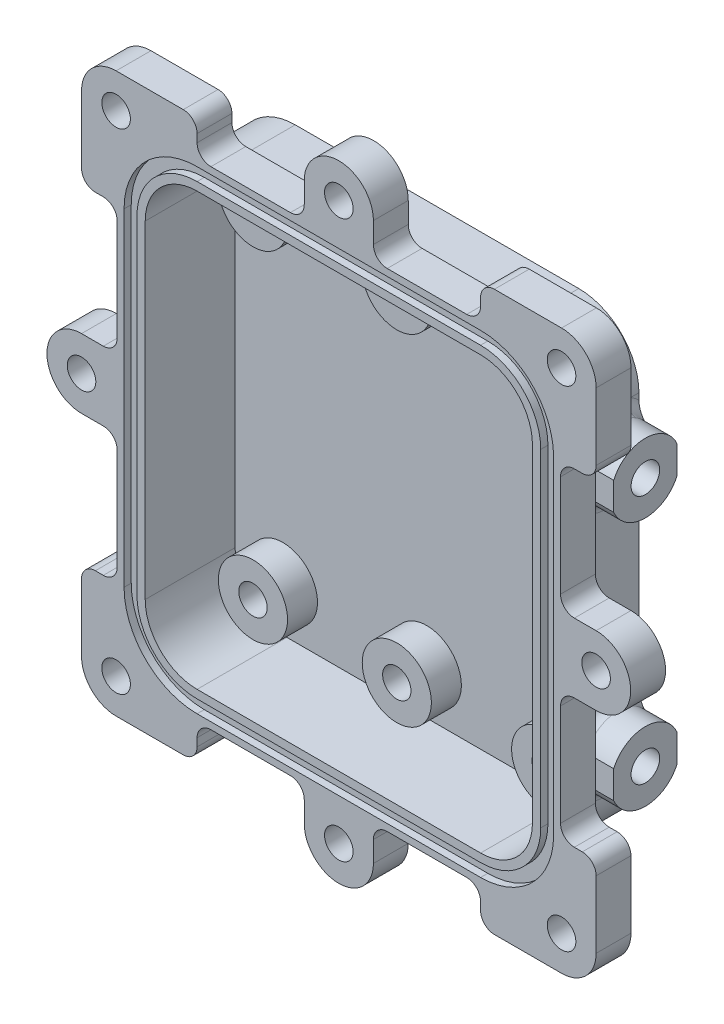
SolidWorks part; units mm, degrees
material "ABS"
ref_plane "X-Y Datum" through (0, 0, 0) normal (0, 0, 1) x (1, 0, 0)
ref_plane "X-Z Datum" through (0, 0, 0) normal (0, 1, 0) x (1, 0, 0)
ref_plane "Y-Z Datum" through (0, 0, 0) normal (1, 0, 0) x (0, 0, -1)
sketch "Sketch1" plane through (0, 0, 0) normal (0, 0, 1) x (1, 0, 0)
  line L0 (26.035, 143.51) -> (78.105, 143.51)
  line L5 (20.066, 67.818) -> (84.074, 67.818) construction
  line L6 (20.066, 67.818) -> (20.066, 139.954) construction
  line L7 (20.066, 139.954) -> (84.074, 139.954) construction
  line L8 (84.074, 67.818) -> (84.074, 139.954) construction
  line L9 (20.066, 67.818) -> (84.074, 139.954) construction
  line L10 (20.066, 139.954) -> (84.074, 67.818) construction
  line L11 (87.63, 73.787) -> (87.63, 133.985)
  line L12 (26.035, 64.262) -> (78.105, 64.262)
  line L13 (16.51, 73.787) -> (16.51, 133.985)
  line L14 (16.51, 143.51) -> (87.63, 143.51) construction
  line L15 (87.63, 64.262) -> (87.63, 143.51) construction
  line L16 (16.51, 64.262) -> (87.63, 64.262) construction
  line L17 (16.51, 64.262) -> (16.51, 143.51) construction
  circle A0 centre (25.292, 135.128) radius 2.1 construction
  circle A1 centre (51.708, 135.128) radius 2.1 construction
  circle A2 centre (79.14, 135.128) radius 2.1 construction
  circle A3 centre (51.708, 72.644) radius 2.1 construction
  circle A4 centre (79.14, 72.644) radius 2.1 construction
  circle A5 centre (25.292, 72.644) radius 2.1 construction
  arc A6 (78.105, 143.51) -> (87.63, 133.985) centre (78.105, 133.985) cw
  arc A7 (87.63, 73.787) -> (78.105, 64.262) centre (78.105, 73.787) cw
  arc A8 (26.035, 64.262) -> (16.51, 73.787) centre (26.035, 73.787) cw
  arc A9 (26.035, 143.51) -> (16.51, 133.985) centre (26.035, 133.985) ccw
  point P18 (52.07, 103.886)
  dimension "D2" = 9.525
  dimension "D1" = 3.556
extrude "Boss-Extrude1" add sketch "Sketch1" along normal blind 16.51 contours L13 A9 L0 A6 L11 A7 L12 A8
shell "Shell1" thickness 1.524
sketch "Sketch2" plane through (0, 0, 0) normal (0, 0, 1) x (1, 0, 0)
  circle A0 centre (25.292, 135.128) radius 6.35
  circle A1 centre (51.708, 135.128) radius 6.35
  circle A3 centre (79.14, 135.128) radius 6.35
  circle A4 centre (25.292, 72.644) radius 6.35
  circle A5 centre (51.708, 72.644) radius 6.35
  circle A6 centre (79.14, 72.644) radius 6.35
  circle A7 centre (25.292, 135.128) radius 2.608
  circle A8 centre (51.708, 135.128) radius 2.608
  circle A9 centre (79.14, 135.128) radius 2.608
  circle A10 centre (25.292, 72.644) radius 2.608
  circle A11 centre (51.708, 72.644) radius 2.608
  circle A12 centre (79.14, 72.644) radius 2.608
extrude "Boss-Extrude2" add sketch "Sketch2" along normal blind 5.5
sketch "Sketch7" plane through (0, 0, 16.51) normal (0, 0, 1) x (1, 0, 0)
  line L17 (78.105, 145.034) -> (26.035, 145.034)
  line L18 (14.986, 133.985) -> (14.986, 73.787)
  line L19 (26.035, 62.738) -> (78.105, 62.738)
  line L20 (89.154, 73.787) -> (89.154, 133.985)
  line L21 (12.6238, 133.985) -> (12.6238, 73.787)
  line L22 (26.035, 60.3758) -> (78.105, 60.3758)
  line L23 (91.5162, 73.787) -> (91.5162, 133.985)
  line L24 (78.105, 147.3962) -> (26.035, 147.3962)
  line L25 (12.6238, 133.985) -> (12.6238, 73.787)
  line L26 (26.035, 60.3758) -> (78.105, 60.3758)
  line L27 (91.5162, 73.787) -> (91.5162, 133.985)
  line L28 (78.105, 147.3962) -> (26.035, 147.3962)
  line L29 (78.105, 148.6662) -> (26.035, 148.6662)
  line L30 (11.3538, 133.985) -> (11.3538, 73.787)
  line L31 (26.035, 59.1058) -> (78.105, 59.1058)
  line L32 (92.7862, 73.787) -> (92.7862, 133.985)
  arc A22 (26.035, 145.034) -> (14.986, 133.985) centre (26.035, 133.985) ccw
  arc A23 (14.986, 73.787) -> (26.035, 62.738) centre (26.035, 73.787) ccw
  arc A24 (78.105, 62.738) -> (89.154, 73.787) centre (78.105, 73.787) ccw
  arc A25 (26.035, 148.6662) -> (11.3538, 133.985) centre (26.035, 133.985) ccw
  arc A26 (12.6238, 73.787) -> (26.035, 60.3758) centre (26.035, 73.787) ccw
  arc A27 (78.105, 60.3758) -> (91.5162, 73.787) centre (78.105, 73.787) ccw
  arc A28 (91.5162, 133.985) -> (78.105, 147.3962) centre (78.105, 133.985) ccw
  arc A29 (26.035, 147.3962) -> (12.6238, 133.985) centre (26.035, 133.985) ccw
  arc A30 (12.6238, 73.787) -> (26.035, 60.3758) centre (26.035, 73.787) ccw
  arc A31 (78.105, 60.3758) -> (91.5162, 73.787) centre (78.105, 73.787) ccw
  arc A32 (91.5162, 133.985) -> (78.105, 147.3962) centre (78.105, 133.985) ccw
  arc A33 (26.035, 147.3962) -> (12.6238, 133.985) centre (26.035, 133.985) ccw
  arc A34 (11.3538, 73.787) -> (26.035, 59.1058) centre (26.035, 73.787) ccw
  arc A35 (78.105, 59.1058) -> (92.7862, 73.787) centre (78.105, 73.787) ccw
  arc A36 (92.7862, 133.985) -> (78.105, 148.6662) centre (78.105, 133.985) ccw
  dimension "D1" = 2.3622
  dimension "D2" = 2.3622
  dimension "D3" = 1.27
extrude "Boss-Extrude9" add sketch "Sketch7" against normal blind 1.3208 separate body contours L32 A36 L29 A25 L30 A34 L31 A35 A33 L28 A32 L27 A31 L26 A30 L25
sketch "Sketch8" plane through (0, 0, 15.1892) normal (0, 0, -1) x (-1, 0, 0)
  line L8 (-11.3538, 73.787) -> (-11.3538, 133.985)
  line L9 (-26.035, 148.6662) -> (-78.105, 148.6662)
  line L10 (-11.3538, 73.787) -> (-11.3538, 133.985)
  line L11 (-26.035, 148.6662) -> (-78.105, 148.6662)
  line L13 (-92.7862, 73.787) -> (-92.7862, 133.985)
  line L14 (-92.7862, 73.787) -> (-92.7862, 133.985)
  line L16 (-26.035, 59.1058) -> (-78.105, 59.1058)
  line L17 (-26.035, 59.1058) -> (-78.105, 59.1058)
  line L20 (-26.035, 145.034) -> (-78.105, 145.034)
  line L21 (-26.035, 145.034) -> (-78.105, 145.034)
  line L33 (-89.154, 133.985) -> (-89.154, 73.787)
  line L34 (-78.105, 62.738) -> (-26.035, 62.738)
  line L35 (-14.986, 73.787) -> (-14.986, 133.985)
  line L36 (-89.154, 133.985) -> (-89.154, 73.787)
  line L37 (-78.105, 62.738) -> (-26.035, 62.738)
  line L38 (-14.986, 73.787) -> (-14.986, 133.985)
  arc A11 (-92.7862, 73.787) -> (-78.105, 59.1058) centre (-78.105, 73.787) ccw
  arc A12 (-26.035, 59.1058) -> (-11.3538, 73.787) centre (-26.035, 73.787) ccw
  arc A13 (-11.3538, 133.985) -> (-26.035, 148.6662) centre (-26.035, 133.985) ccw
  arc A14 (-78.105, 148.6662) -> (-92.7862, 133.985) centre (-78.105, 133.985) ccw
  arc A15 (-26.035, 59.1058) -> (-11.3538, 73.787) centre (-26.035, 73.787) ccw
  arc A16 (-11.3538, 133.985) -> (-26.035, 148.6662) centre (-26.035, 133.985) ccw
  arc A17 (-78.105, 148.6662) -> (-92.7862, 133.985) centre (-78.105, 133.985) ccw
  arc A18 (-92.7862, 73.787) -> (-78.105, 59.1058) centre (-78.105, 73.787) ccw
  arc A24 (-14.986, 133.985) -> (-26.035, 145.034) centre (-26.035, 133.985) ccw
  arc A25 (-78.105, 145.034) -> (-89.154, 133.985) centre (-78.105, 133.985) ccw
  arc A26 (-14.986, 133.985) -> (-26.035, 145.034) centre (-26.035, 133.985) ccw
  arc A27 (-78.105, 145.034) -> (-89.154, 133.985) centre (-78.105, 133.985) ccw
  arc A32 (-78.105, 145.034) -> (-89.154, 133.985) centre (-78.105, 133.985) ccw
  arc A34 (-89.154, 73.787) -> (-78.105, 62.738) centre (-78.105, 73.787) ccw
  arc A35 (-26.035, 62.738) -> (-14.986, 73.787) centre (-26.035, 73.787) ccw
  arc A36 (-89.154, 73.787) -> (-78.105, 62.738) centre (-78.105, 73.787) ccw
  arc A37 (-26.035, 62.738) -> (-14.986, 73.787) centre (-26.035, 73.787) ccw
  arc M17 (-26.035, 147.3962) -> (-12.6238, 133.985) centre (-26.035, 133.985) cw
  line M18 (-12.6238, 133.985) -> (-12.6238, 73.787)
  arc M19 (-12.6238, 73.787) -> (-26.035, 60.3758) centre (-26.035, 73.787) cw
  line M20 (-26.035, 60.3758) -> (-78.105, 60.3758)
  arc M21 (-78.105, 60.3758) -> (-91.5162, 73.787) centre (-78.105, 73.787) cw
  line M22 (-91.5162, 73.787) -> (-91.5162, 133.985)
  arc M23 (-91.5162, 133.985) -> (-78.105, 147.3962) centre (-78.105, 133.985) cw
  line M24 (-78.105, 147.3962) -> (-26.035, 147.3962)
  line M25 (-92.7862, 133.985) -> (-92.7862, 73.787)
  arc M26 (-92.7862, 73.787) -> (-78.105, 59.1058) centre (-78.105, 73.787) ccw
  line M27 (-78.105, 59.1058) -> (-26.035, 59.1058)
  arc M28 (-26.035, 59.1058) -> (-11.3538, 73.787) centre (-26.035, 73.787) ccw
  line M29 (-11.3538, 73.787) -> (-11.3538, 133.985)
  arc M30 (-11.3538, 133.985) -> (-26.035, 148.6662) centre (-26.035, 133.985) ccw
  line M31 (-26.035, 148.6662) -> (-78.105, 148.6662)
  arc M32 (-78.105, 148.6662) -> (-92.7862, 133.985) centre (-78.105, 133.985) ccw
  dimension "D1" = 0
  dimension "D2" = 0
  dimension "D3" = 0
  dimension "D4" = 0
  dimension "D5" = 0
  dimension "D6" = 0
extrude "Boss-Extrude10" add sketch "Sketch8" along normal blind 5.08 contours M32 M25 M26 M27 M28 M29 M30 M31 M24 M17 M18 M19 M20 M21 M22 M23 | A37 L37 A36 L36 A27 L21 A26 L38 M17 M24 M23 M22 M21 M20 M19 M18
sketch "Sketch9" plane through (0, 0, 16.51) normal (0, 0, 1) x (1, 0, 0)
  line L0 (78.105, 148.6662) -> (26.035, 148.6662) construction
  line L1 (11.3538, 103.886) -> (106.4794, 103.886) construction
  line L2 (11.1637, 155.2063) -> (26.035, 155.2063)
  line L3 (52.07, 64.262) -> (52.07, 112.9369) construction
  line L4 (26.035, 155.2063) -> (26.035, 148.6662)
  line L5 (4.8137, 148.8563) -> (4.8137, 133.985)
  line L6 (11.3538, 133.985) -> (4.8137, 133.985)
  line L7 (45.72, 155.0162) -> (45.72, 148.6662)
  line L8 (45.72, 148.6662) -> (58.42, 148.6662)
  line L9 (58.42, 148.6662) -> (58.42, 155.0162)
  line L10 (4.8137, 110.236) -> (11.3538, 110.236)
  line L11 (11.3538, 133.985) -> (11.3538, 73.787) construction
  line L12 (11.3538, 110.236) -> (11.3538, 97.536)
  line L13 (11.3538, 97.536) -> (4.8137, 97.536)
  line L14 (92.7862, 133.985) -> (99.3263, 133.985)
  line L15 (99.3263, 148.8563) -> (99.3263, 133.985)
  line L16 (92.9763, 155.2063) -> (78.105, 155.2063)
  line L17 (78.105, 155.2063) -> (78.105, 148.6662)
  line L18 (78.105, 52.5657) -> (78.105, 59.1058)
  line L19 (92.9763, 52.5657) -> (78.105, 52.5657)
  line L20 (99.3263, 58.9157) -> (99.3263, 73.787)
  line L21 (92.7862, 73.787) -> (99.3263, 73.787)
  line L22 (58.42, 59.1058) -> (58.42, 52.7558)
  line L23 (45.72, 59.1058) -> (58.42, 59.1058)
  line L24 (45.72, 52.7558) -> (45.72, 59.1058)
  line L25 (11.3538, 73.787) -> (4.8137, 73.787)
  line L26 (4.8137, 58.9157) -> (4.8137, 73.787)
  line L27 (11.1637, 52.5657) -> (26.035, 52.5657)
  line L28 (26.035, 52.5657) -> (26.035, 59.1058)
  line L29 (99.3263, 110.236) -> (92.7862, 110.236)
  line L30 (92.7862, 97.536) -> (99.3263, 97.536)
  line L31 (92.7862, 110.236) -> (92.7862, 97.536)
  arc A0 (11.1637, 155.2063) -> (4.8137, 148.8563) centre (11.1637, 148.8563) ccw
  arc A2 (26.035, 148.6662) -> (11.3538, 133.985) centre (26.035, 133.985) ccw construction
  arc A3 (58.42, 155.0162) -> (45.72, 155.0162) centre (52.07, 155.0162) ccw
  arc A8 (4.8137, 110.236) -> (4.8137, 97.536) centre (4.8137, 103.886) ccw
  arc A10 (11.3538, 133.985) -> (26.035, 148.6662) centre (26.035, 133.985) cw
  circle A11 centre (11.1637, 148.8563) radius 2.625
  circle A12 centre (52.07, 155.0162) radius 2.625
  circle A13 centre (4.8137, 103.886) radius 2.625
  circle A14 centre (92.9763, 148.8563) radius 2.625
  arc A15 (92.9763, 155.2063) -> (99.3263, 148.8563) centre (92.9763, 148.8563) cw
  arc A16 (92.7862, 133.985) -> (78.105, 148.6662) centre (78.105, 133.985) ccw
  circle A17 centre (92.9763, 58.9157) radius 2.625
  arc A18 (92.7862, 73.787) -> (78.105, 59.1058) centre (78.105, 73.787) cw
  arc A19 (92.9763, 52.5657) -> (99.3263, 58.9157) centre (92.9763, 58.9157) ccw
  circle A20 centre (52.07, 52.7558) radius 2.625
  arc A21 (58.42, 52.7558) -> (45.72, 52.7558) centre (52.07, 52.7558) cw
  circle A22 centre (11.1637, 58.9157) radius 2.625
  arc A23 (11.1637, 52.5657) -> (4.8137, 58.9157) centre (11.1637, 58.9157) cw
  arc A24 (11.3538, 73.787) -> (26.035, 59.1058) centre (26.035, 73.787) ccw
  circle A25 centre (99.3263, 103.886) radius 2.625
  arc A26 (99.3263, 110.236) -> (99.3263, 97.536) centre (99.3263, 103.886) cw
  point P4 (15.6538, 144.3662)
  point P5 (52.07, 148.6662)
  point P7 (15.6538, 144.3662)
extrude "Boss-Extrude11" add sketch "Sketch9" against normal up to surface (6.4008 mm away)
fillet "Fillet2" radius 2.54 24 edges at (78.105, 148.6662, 13.3096) (92.7862, 133.985, 13.3096) (92.7862, 73.787, 13.3096) (78.105, 59.1058, 13.3096) (26.035, 59.1058, 13.3096) (11.3538, 73.787, 13.3096) (11.3538, 133.985, 13.3096) (26.035, 148.6662, 13.3096) (58.42, 148.6662, 13.3096) (45.72, 148.6662, 13.3096) (11.3538, 110.236, 13.3096) (11.3538, 97.536, 13.3096) (99.3263, 73.787, 13.3096) (78.105, 52.5657, 13.3096) (26.035, 155.2063, 13.3096) (4.8137, 133.985, 13.3096) (78.105, 155.2063, 13.3096) (99.3263, 133.985, 13.3096) (45.72, 59.1058, 13.3096) (58.42, 59.1058, 13.3096) (26.035, 52.5657, 13.3096) (4.8137, 73.787, 13.3096) (92.7862, 97.536, 13.3096) (92.7862, 110.236, 13.3096)
sketch "Sketch10" plane through (89.154, 0, 0) normal (1, 0, 0) x (0, 0, -1)
  line L0 (-10.1092, 129.3678) -> (-10.1092, 124.2728)
  line L3 (1.524, 129.3678) -> (1.524, 124.2728)
  line L5 (1.524, 103.886) -> (-29.2885, 103.886) construction
  line L6 (1.524, 73.787) -> (1.524, 133.985) construction
  line L7 (-10.1092, 78.4042) -> (-10.1092, 83.4992)
  line L8 (1.524, 78.4042) -> (1.524, 83.4992)
  arc A0 (-10.1092, 124.2728) -> (1.524, 124.2728) centre (-4.2926, 126.8203) ccw
  arc A1 (1.524, 129.3678) -> (-10.1092, 129.3678) centre (-4.2926, 126.8203) ccw
  arc A2 (1.524, 78.4042) -> (-10.1092, 78.4042) centre (-4.2926, 80.9517) cw
  arc A3 (-10.1092, 83.4992) -> (1.524, 83.4992) centre (-4.2926, 80.9517) cw
  circle A4 centre (-4.2926, 126.8203) radius 2.625
  circle A5 centre (-4.2926, 80.9517) radius 2.625
extrude "Boss-Extrude12" add sketch "Sketch10" along normal blind 7
ref_plane "Plane1" through (52.07, 0, 0) normal (1, 0, 0) x (0, 0, -1)
mirror "Mirror1" about plane through (52.07, 0, 0) normal (1, 0, 0) of "Boss-Extrude12"
fillet "Fillet3" radius 2 8 edges at (89.154, 120.4703, 4.2926) (89.154, 133.1703, 4.2926) (89.154, 87.3017, 4.2926) (89.154, 74.6017, 4.2926) (14.986, 74.6017, 4.2926) (14.986, 87.3017, 4.2926) (14.986, 120.4703, 4.2926) (14.986, 133.1703, 4.2926)
sketch "Sketch11" plane through (7.986, 0, 0) normal (-1, 0, 0) x (0, 0, 1)
  line L5 (7.5537, 70.7143) -> (-1.524, 70.7143)
  line L6 (7.5537, 70.7143) -> (7.5537, 161.5706)
  line L7 (7.5537, 161.5706) -> (-1.524, 161.5706)
  line L8 (-1.524, 70.7143) -> (-1.524, 161.5706)
  circle A0 centre (4.2926, 126.8203) radius 2.1
  circle A1 centre (4.2926, 80.9517) radius 2.1
sketch "Sketch12" plane through (0, 0, 16.51) normal (0, 0, 1) x (1, 0, 0)
  line L8 (4.8137, 148.8563) -> (4.8137, 136.525)
  line L9 (23.495, 155.2063) -> (11.1637, 155.2063)
  line L10 (4.8137, 148.8563) -> (4.8137, 136.525)
  line L11 (23.495, 155.2063) -> (11.1637, 155.2063)
  line L12 (8.8138, 133.985) -> (7.3537, 133.985)
  line L13 (8.8138, 133.985) -> (7.3537, 133.985)
  line L31 (7.3537, 73.787) -> (8.8138, 73.787)
  line L32 (7.3537, 73.787) -> (8.8138, 73.787)
  line L33 (11.3538, 94.996) -> (11.3538, 76.327)
  line L34 (4.8137, 97.536) -> (8.8138, 97.536)
  line L35 (8.8138, 110.236) -> (4.8137, 110.236)
  line L36 (11.3538, 131.445) -> (11.3538, 112.776)
  line L37 (11.3538, 94.996) -> (11.3538, 76.327)
  line L38 (4.8137, 97.536) -> (8.8138, 97.536)
  line L39 (8.8138, 110.236) -> (4.8137, 110.236)
  line L40 (11.3538, 131.445) -> (11.3538, 112.776)
  line L73 (58.42, 52.7558) -> (58.42, 56.5658)
  line L74 (58.42, 52.7558) -> (58.42, 56.5658)
  line L75 (45.72, 56.5658) -> (45.72, 52.7558)
  line L76 (28.575, 59.1058) -> (43.18, 59.1058)
  line L77 (26.035, 55.1057) -> (26.035, 56.5658)
  line L78 (11.1637, 52.5657) -> (23.495, 52.5657)
  line L79 (4.8137, 71.247) -> (4.8137, 58.9157)
  line L80 (45.72, 56.5658) -> (45.72, 52.7558)
  line L81 (28.575, 59.1058) -> (43.18, 59.1058)
  line L82 (26.035, 55.1057) -> (26.035, 56.5658)
  line L83 (11.1637, 52.5657) -> (23.495, 52.5657)
  line L84 (4.8137, 71.247) -> (4.8137, 58.9157)
  line L108 (99.3263, 58.9157) -> (99.3263, 71.247)
  line L109 (80.645, 52.5657) -> (92.9763, 52.5657)
  line L110 (78.105, 56.5658) -> (78.105, 55.1057)
  line L111 (60.96, 59.1058) -> (75.565, 59.1058)
  line L112 (99.3263, 58.9157) -> (99.3263, 71.247)
  line L113 (80.645, 52.5657) -> (92.9763, 52.5657)
  line L114 (78.105, 56.5658) -> (78.105, 55.1057)
  line L115 (60.96, 59.1058) -> (75.565, 59.1058)
  line L118 (92.7862, 76.327) -> (92.7862, 94.996)
  line L119 (96.7863, 73.787) -> (95.3262, 73.787)
  line L120 (92.7862, 76.327) -> (92.7862, 94.996)
  line L121 (96.7863, 73.787) -> (95.3262, 73.787)
  line L135 (92.7862, 131.445) -> (92.7862, 112.776)
  line L136 (95.3262, 110.236) -> (99.3263, 110.236)
  line L137 (99.3263, 97.536) -> (95.3262, 97.536)
  line L138 (92.7862, 131.445) -> (92.7862, 112.776)
  line L139 (95.3262, 110.236) -> (99.3263, 110.236)
  line L140 (99.3263, 97.536) -> (95.3262, 97.536)
  line L181 (92.9763, 155.2063) -> (80.645, 155.2063)
  line L182 (99.3263, 136.525) -> (99.3263, 148.8563)
  line L183 (95.3262, 133.985) -> (96.7863, 133.985)
  line L184 (92.9763, 155.2063) -> (80.645, 155.2063)
  line L185 (99.3263, 136.525) -> (99.3263, 148.8563)
  line L186 (95.3262, 133.985) -> (96.7863, 133.985)
  line L190 (75.565, 148.6662) -> (60.96, 148.6662)
  line L191 (78.105, 152.6663) -> (78.105, 151.2062)
  line L192 (75.565, 148.6662) -> (60.96, 148.6662)
  line L193 (78.105, 152.6663) -> (78.105, 151.2062)
  line L216 (26.035, 152.6663) -> (26.035, 151.2062)
  line L217 (28.575, 148.6662) -> (43.18, 148.6662)
  line L218 (45.72, 151.2062) -> (45.72, 155.0162)
  line L219 (58.42, 155.0162) -> (58.42, 151.2062)
  line L220 (26.035, 152.6663) -> (26.035, 151.2062)
  line L221 (28.575, 148.6662) -> (43.18, 148.6662)
  line L222 (45.72, 151.2062) -> (45.72, 155.0162)
  line L223 (58.42, 155.0162) -> (58.42, 151.2062)
  circle A0 centre (11.1637, 148.8563) radius 2.625
  circle A1 centre (92.9763, 148.8563) radius 2.625
  circle A2 centre (52.07, 155.0162) radius 2.625
  circle A3 centre (99.3263, 103.886) radius 2.625
  circle A4 centre (92.9763, 58.9157) radius 2.625
  circle A5 centre (52.07, 52.7558) radius 2.625
  circle A6 centre (11.1637, 58.9157) radius 2.625
  circle A7 centre (4.8137, 103.886) radius 2.625
  arc A14 (4.8137, 136.525) -> (7.3537, 133.985) centre (7.3537, 136.525) ccw
  arc A15 (11.1637, 155.2063) -> (4.8137, 148.8563) centre (11.1637, 148.8563) ccw
  arc A16 (4.8137, 136.525) -> (7.3537, 133.985) centre (7.3537, 136.525) ccw
  arc A17 (11.1637, 155.2063) -> (4.8137, 148.8563) centre (11.1637, 148.8563) ccw
  arc A19 (11.3538, 131.445) -> (8.8138, 133.985) centre (8.8138, 131.445) ccw
  arc A20 (11.3538, 131.445) -> (8.8138, 133.985) centre (8.8138, 131.445) ccw
  arc A35 (11.3538, 94.996) -> (8.8138, 97.536) centre (8.8138, 94.996) ccw
  arc A36 (4.8137, 110.236) -> (4.8137, 97.536) centre (4.8137, 103.886) ccw
  arc A37 (8.8138, 110.236) -> (11.3538, 112.776) centre (8.8138, 112.776) ccw
  arc A38 (11.3538, 94.996) -> (8.8138, 97.536) centre (8.8138, 94.996) ccw
  arc A39 (4.8137, 110.236) -> (4.8137, 97.536) centre (4.8137, 103.886) ccw
  arc A40 (8.8138, 110.236) -> (11.3538, 112.776) centre (8.8138, 112.776) ccw
  arc A41 (8.8138, 73.787) -> (11.3538, 76.327) centre (8.8138, 76.327) ccw
  arc A42 (8.8138, 73.787) -> (11.3538, 76.327) centre (8.8138, 76.327) ccw
  arc A80 (60.96, 59.1058) -> (58.42, 56.5658) centre (60.96, 56.5658) ccw
  arc A81 (60.96, 59.1058) -> (58.42, 56.5658) centre (60.96, 56.5658) ccw
  arc A84 (45.72, 52.7558) -> (58.42, 52.7558) centre (52.07, 52.7558) ccw
  arc A85 (45.72, 56.5658) -> (43.18, 59.1058) centre (43.18, 56.5658) ccw
  arc A86 (28.575, 59.1058) -> (26.035, 56.5658) centre (28.575, 56.5658) ccw
  arc A87 (23.495, 52.5657) -> (26.035, 55.1057) centre (23.495, 55.1057) ccw
  arc A88 (4.8137, 58.9157) -> (11.1637, 52.5657) centre (11.1637, 58.9157) ccw
  arc A89 (7.3537, 73.787) -> (4.8137, 71.247) centre (7.3537, 71.247) ccw
  arc A90 (45.72, 52.7558) -> (58.42, 52.7558) centre (52.07, 52.7558) ccw
  arc A91 (45.72, 56.5658) -> (43.18, 59.1058) centre (43.18, 56.5658) ccw
  arc A92 (28.575, 59.1058) -> (26.035, 56.5658) centre (28.575, 56.5658) ccw
  arc A93 (23.495, 52.5657) -> (26.035, 55.1057) centre (23.495, 55.1057) ccw
  arc A94 (4.8137, 58.9157) -> (11.1637, 52.5657) centre (11.1637, 58.9157) ccw
  arc A95 (7.3537, 73.787) -> (4.8137, 71.247) centre (7.3537, 71.247) ccw
  arc A112 (92.7862, 76.327) -> (95.3262, 73.787) centre (95.3262, 76.327) ccw
  arc A113 (99.3263, 71.247) -> (96.7863, 73.787) centre (96.7863, 71.247) ccw
  arc A114 (92.9763, 52.5657) -> (99.3263, 58.9157) centre (92.9763, 58.9157) ccw
  arc A115 (78.105, 55.1057) -> (80.645, 52.5657) centre (80.645, 55.1057) ccw
  arc A116 (78.105, 56.5658) -> (75.565, 59.1058) centre (75.565, 56.5658) ccw
  arc A117 (99.3263, 71.247) -> (96.7863, 73.787) centre (96.7863, 71.247) ccw
  arc A118 (92.9763, 52.5657) -> (99.3263, 58.9157) centre (92.9763, 58.9157) ccw
  arc A119 (78.105, 55.1057) -> (80.645, 52.5657) centre (80.645, 55.1057) ccw
  arc A120 (78.105, 56.5658) -> (75.565, 59.1058) centre (75.565, 56.5658) ccw
  arc A121 (92.7862, 76.327) -> (95.3262, 73.787) centre (95.3262, 76.327) ccw
  arc A141 (95.3262, 133.985) -> (92.7862, 131.445) centre (95.3262, 131.445) ccw
  arc A142 (92.7862, 112.776) -> (95.3262, 110.236) centre (95.3262, 112.776) ccw
  arc A143 (99.3263, 97.536) -> (99.3263, 110.236) centre (99.3263, 103.886) ccw
  arc A144 (95.3262, 97.536) -> (92.7862, 94.996) centre (95.3262, 94.996) ccw
  arc A145 (95.3262, 133.985) -> (92.7862, 131.445) centre (95.3262, 131.445) ccw
  arc A146 (92.7862, 112.776) -> (95.3262, 110.236) centre (95.3262, 112.776) ccw
  arc A147 (99.3263, 97.536) -> (99.3263, 110.236) centre (99.3263, 103.886) ccw
  arc A148 (95.3262, 97.536) -> (92.7862, 94.996) centre (95.3262, 94.996) ccw
  arc A186 (99.3263, 148.8563) -> (92.9763, 155.2063) centre (92.9763, 148.8563) ccw
  arc A187 (96.7863, 133.985) -> (99.3263, 136.525) centre (96.7863, 136.525) ccw
  arc A188 (99.3263, 148.8563) -> (92.9763, 155.2063) centre (92.9763, 148.8563) ccw
  arc A189 (96.7863, 133.985) -> (99.3263, 136.525) centre (96.7863, 136.525) ccw
  arc A196 (75.565, 148.6662) -> (78.105, 151.2062) centre (75.565, 151.2062) ccw
  arc A197 (80.645, 155.2063) -> (78.105, 152.6663) centre (80.645, 152.6663) ccw
  arc A198 (75.565, 148.6662) -> (78.105, 151.2062) centre (75.565, 151.2062) ccw
  arc A199 (80.645, 155.2063) -> (78.105, 152.6663) centre (80.645, 152.6663) ccw
  arc A228 (26.035, 152.6663) -> (23.495, 155.2063) centre (23.495, 152.6663) ccw
  arc A229 (26.035, 151.2062) -> (28.575, 148.6662) centre (28.575, 151.2062) ccw
  arc A230 (43.18, 148.6662) -> (45.72, 151.2062) centre (43.18, 151.2062) ccw
  arc A231 (58.42, 155.0162) -> (45.72, 155.0162) centre (52.07, 155.0162) ccw
  arc A232 (58.42, 151.2062) -> (60.96, 148.6662) centre (60.96, 151.2062) ccw
  arc A233 (26.035, 152.6663) -> (23.495, 155.2063) centre (23.495, 152.6663) ccw
  arc A234 (26.035, 151.2062) -> (28.575, 148.6662) centre (28.575, 151.2062) ccw
  arc A235 (43.18, 148.6662) -> (45.72, 151.2062) centre (43.18, 151.2062) ccw
  arc A236 (58.42, 155.0162) -> (45.72, 155.0162) centre (52.07, 155.0162) ccw
  arc A237 (58.42, 151.2062) -> (60.96, 148.6662) centre (60.96, 151.2062) ccw
  dimension "D1" = 0
  dimension "D2" = 0
  dimension "D3" = 0
  dimension "D4" = 0
  dimension "D5" = 0
  dimension "D6" = 0
  dimension "D7" = 0
  dimension "D8" = 0
  dimension "D9" = 0
  dimension "D10" = 0
  dimension "D11" = 0
  dimension "D12" = 0
sketch "Sketch13" plane through (0, 0, 16.51) normal (0, 0, 1) x (1, 0, 0)
  line L0 (78.105, 145.034) -> (78.105, 143.51)
  line L1 (87.63, 133.985) -> (89.154, 133.985)
  line L2 (52.07, -6.3983) -> (52.07, 6.3983) construction
  line L3 (15.748, 63.5) -> (88.392, 63.5)
  line L4 (15.748, 63.5) -> (15.748, 144.272)
  line L5 (15.748, 144.272) -> (88.392, 144.272)
  line L6 (88.392, 63.5) -> (88.392, 144.272)
  line L7 (15.748, 63.5) -> (88.392, 144.272) construction
  line L8 (15.748, 144.272) -> (88.392, 63.5) construction
  point P8 (52.07, 103.886)
